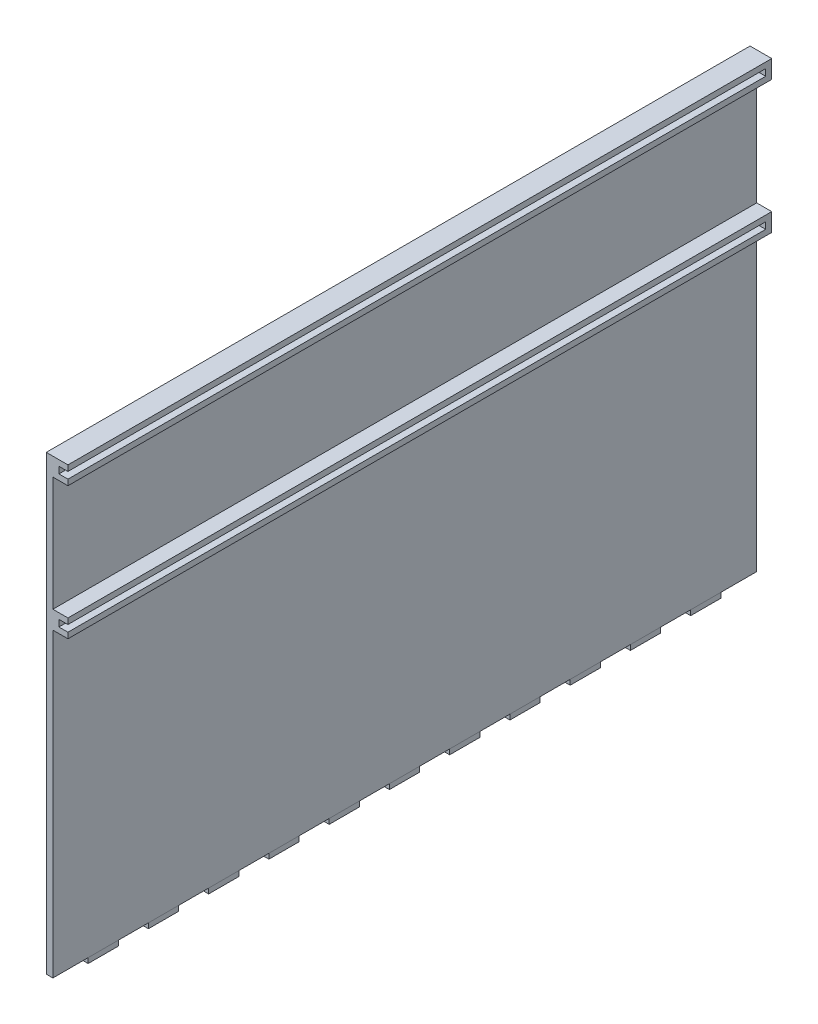
SolidWorks part; units mm, degrees
ref_plane "Front Plane" through (0, 0, 0) normal (0, 0, 1) x (1, 0, 0)
ref_plane "Top Plane" through (0, 0, 0) normal (0, 1, 0) x (1, 0, 0)
ref_plane "Right Plane" through (0, 0, 0) normal (1, 0, 0) x (0, 0, -1)
sketch "草图4" plane through (0, 0, 0) normal (1, 0, 0) x (0, 0, -1)
  line L1 (116.8, -75) -> (-116.8, -75)
  line L2 (116.8, -75) -> (116.8, 75)
  line L3 (116.8, 75) -> (-116.8, 75)
  line L4 (-116.8, -75) -> (-116.8, 75)
  line L5 (116.8, -75) -> (-116.8, 75) construction
  line L6 (116.8, 75) -> (-116.8, -75) construction
  point P0 (0, 0)
  dimension "D1" = 233.6
  dimension "D2" = 150
extrude "凸台-拉伸2" add sketch "草图4" along normal blind 2.2
sketch "草图6" plane through (0, -75, 0) normal (0, -1, 0) x (1, 0, 0)
  line L6 (2.1, 15) -> (2.1, 25)
  line L10 (2.1, 15) -> (0.1, 15)
  line L11 (2.1, -5) -> (0.1, -5)
  line L12 (2.1, -5) -> (2.1, 5)
  line L13 (2.1, 5) -> (0.1, 5)
  line L14 (0.1, -5) -> (0.1, 5)
  line L15 (2.1, -5) -> (0.1, 5) construction
  line L16 (2.1, 5) -> (0.1, -5) construction
  line L17 (0.1, 15) -> (0.1, 25)
  line L18 (2.1, 25) -> (0.1, 25)
  line L19 (2.1, 35) -> (2.1, 45)
  line L20 (2.1, 35) -> (0.1, 35)
  line L21 (0.1, 35) -> (0.1, 45)
  line L22 (2.1, 45) -> (0.1, 45)
  line L23 (2.1, 55) -> (2.1, 65)
  line L24 (2.1, 55) -> (0.1, 55)
  line L25 (0.1, 55) -> (0.1, 65)
  line L26 (2.1, 65) -> (0.1, 65)
  line L27 (2.1, 75) -> (2.1, 85)
  line L28 (2.1, 75) -> (0.1, 75)
  line L29 (0.1, 75) -> (0.1, 85)
  line L30 (2.1, 85) -> (0.1, 85)
  line L31 (2.1, 95) -> (2.1, 105)
  line L32 (2.1, 95) -> (0.1, 95)
  line L33 (0.1, 95) -> (0.1, 105)
  line L34 (2.1, 105) -> (0.1, 105)
  line L35 (2.1, -25) -> (2.1, -15)
  line L36 (2.1, -25) -> (0.1, -25)
  line L37 (0.1, -25) -> (0.1, -15)
  line L38 (2.1, -15) -> (0.1, -15)
  line L39 (2.1, -45) -> (2.1, -35)
  line L40 (2.1, -45) -> (0.1, -45)
  line L41 (0.1, -45) -> (0.1, -35)
  line L42 (2.1, -35) -> (0.1, -35)
  line L43 (2.1, -65) -> (2.1, -55)
  line L44 (2.1, -65) -> (0.1, -65)
  line L45 (0.1, -65) -> (0.1, -55)
  line L46 (2.1, -55) -> (0.1, -55)
  line L47 (2.1, -85) -> (2.1, -75)
  line L48 (2.1, -85) -> (0.1, -85)
  line L49 (0.1, -85) -> (0.1, -75)
  line L50 (2.1, -75) -> (0.1, -75)
  line L51 (2.1, -105) -> (2.1, -95)
  line L52 (2.1, -105) -> (0.1, -105)
  line L53 (0.1, -105) -> (0.1, -95)
  line L54 (2.1, -95) -> (0.1, -95)
  point P6 (1.1, 0)
  dimension "D1" = 2
  dimension "D2" = 10
  dimension "D3" = 6
extrude "凸台-拉伸3" add sketch "草图6" along normal blind 1.8
sketch "草图7" plane through (2.2, 0, 0) normal (1, 0, 0) x (0, 0, -1)
  line L0 (116.8, 25) -> (-116.8, 25)
  line L5 (-116.8, -75) -> (116.8, -75) construction
  line L6 (116.8, -75) -> (116.8, 75) construction
  line L9 (-116.8, 75) -> (-116.8, -75) construction
  line L14 (-116.8, 31) -> (-116.8, 25)
  line L15 (116.8, 31) -> (116.8, 25)
  line L16 (-116.8, 31) -> (116.8, 31)
  line L17 (116.8, 69) -> (116.8, 75)
  line L18 (-116.8, 69) -> (116.8, 69)
  line L19 (-116.8, 69) -> (-116.8, 75)
  line L20 (116.8, 75) -> (-116.8, 75)
  point P7 (0, 0)
  dimension "D1" = 100
  dimension "D2" = 6
extrude "凸台-拉伸4" add sketch "草图7" along normal blind 5
sketch "草图8" plane through (7.2, 0, 0) normal (1, 0, 0) x (0, 0, -1)
  line L0 (0, 31) -> (0, 25)
  line L1 (116.8, 31) -> (-116.8, 31) construction
  line L2 (-116.8, 25) -> (116.8, 25) construction
  line L3 (-116.8, 31) -> (-116.8, 25) construction
  line L4 (114.8, 29.1) -> (114.8, 26.9)
  line L5 (116.8, 26.9) -> (-116.8, 26.9)
  line L7 (116.8, 29.1) -> (-116.8, 29.1)
  line L8 (-116.8, 26.9) -> (-116.8, 29.1)
  line L9 (116.8, 26.9) -> (-116.8, 29.1) construction
  line L10 (116.8, 29.1) -> (-116.8, 26.9) construction
  line L12 (114.8, 70.9) -> (114.8, 73.1)
  line L18 (-116.8, 73.1) -> (-116.8, 70.9)
  line L19 (116.8, 73.1) -> (-116.8, 73.1)
  line L20 (116.8, 70.9) -> (-116.8, 70.9)
  point P6 (0, 28)
  line M7 (-116.8, 31) -> (-116.8, 25)
  dimension "D1" = 2.2
extrude "切除-拉伸1" cut sketch "草图8" against normal blind 3 contours L4 L7 L0 L5 | L0 L7 L5 M7 | L20 L12 L19 L18
